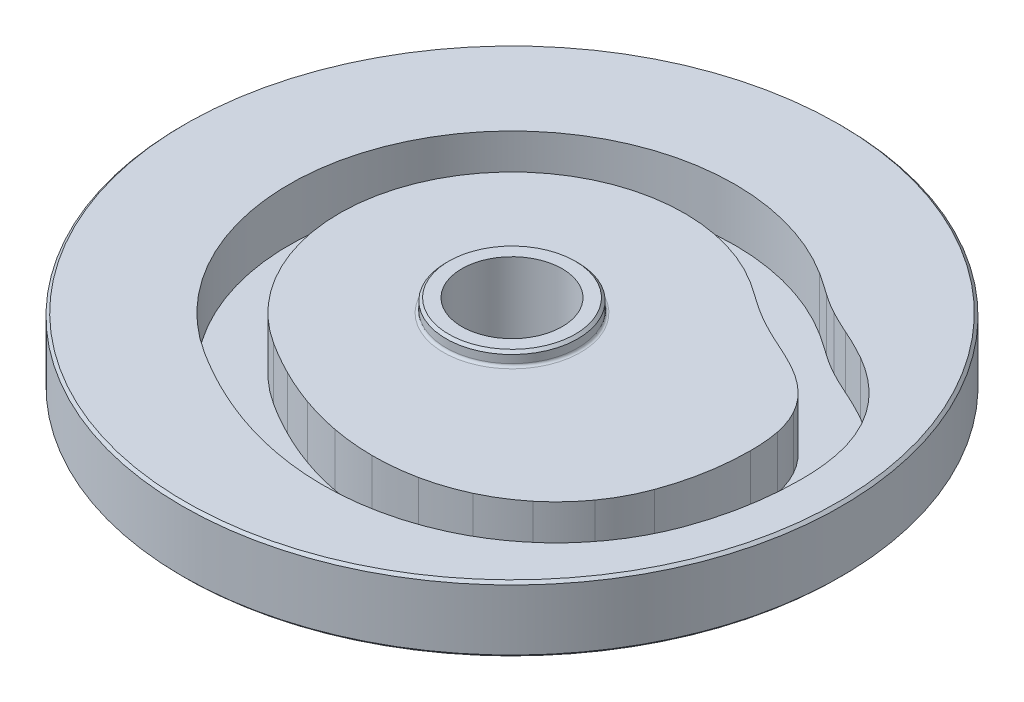
SolidWorks part; units mm, degrees
ref_plane "Front" through (0, 0, 0) normal (0, 0, 1) x (1, 0, 0)
ref_plane "Top" through (0, 0, 0) normal (0, 1, 0) x (1, 0, 0)
ref_plane "Right" through (0, 0, 0) normal (1, 0, 0) x (0, 0, -1)
other "Configuration Table"
sketch "Sketch1" plane through (0, 0, 0) normal (0, 0, 1) x (1, 0, 0)
  line L0 (0, -30350) -> (0, 355) construction
  line L1 (19.05, 5) -> (24, 5)
  line L2 (24, 5) -> (25, 4)
  line L3 (25, 4) -> (25, 1)
  line L4 (26, 0) -> (124, 0)
  line L5 (124, 0) -> (125, -1)
  line L6 (125, -1) -> (125, -24)
  line L7 (125, -24) -> (124, -25)
  line L8 (124, -25) -> (26, -25)
  line L9 (25, -26) -> (25, -29)
  line L10 (25, -29) -> (24, -30)
  line L11 (24, -30) -> (19.05, -30)
  line L12 (19.05, -30) -> (19.05, 5)
  arc A0 (25, 1) -> (26, 0) centre (26, 1) ccw
  arc A1 (26, -25) -> (25, -26) centre (26, -26) ccw
revolve "Base-Revolve" add sketch "Sketch1" angle 360 about L0
sketch "Sketch2" plane through (0, 0, 0) normal (0, 1, 0) x (1, 0, 0)
  line L0 (0, 0) -> (100, 0) construction
  arc A0 (100, 0) -> (98.8357, 13.0115) centre (35.1621, 0.756) ccw
  arc A1 (98.8357, 13.0115) -> (94.4055, 25.2692) centre (56.5582, 4.6609) ccw
  arc A2 (94.4055, 25.2692) -> (86.4082, 35.5582) centre (57.7012, 4.9924) ccw
  arc A3 (86.4082, 35.5582) -> (76.1666, 43.0686) centre (49.5088, -4.0212) ccw
  arc A4 (76.1666, 43.0686) -> (65.7386, 48.2775) centre (17.0985, -62.1401) ccw
  arc A5 (65.7386, 48.2775) -> (56.4654, 52.7493) centre (126.41, 185.9441) cw
  arc A6 (56.4654, 52.7493) -> (48.2764, 57.8032) centre (97.8381, 128.9475) cw
  arc A7 (48.2764, 57.8032) -> (40.2312, 63.2965) centre (-118.4006, -177.6649) ccw
  arc A8 (40.2312, 63.2965) -> (-40.2312, -63.2965) centre (0, 0) ccw
  arc A9 (-40.2312, -63.2965) -> (-27.3421, -70.6474) centre (40.8941, 63.9741) ccw
  arc A10 (-27.3421, -70.6474) -> (-12.9935, -76.8335) centre (29.3243, 41.0558) ccw
  arc A11 (-12.9935, -76.8335) -> (2.9489, -81.1965) centre (23.1016, 23.7507) ccw
  arc A12 (2.9489, -81.1965) -> (20.2342, -82.8956) centre (20.8417, 12.0552) ccw
  arc A13 (20.2342, -82.8956) -> (38.1992, -81.1273) centre (20.7804, 3.6953) ccw
  arc A14 (38.1992, -81.1273) -> (55.8267, -75.3156) centre (22.0381, -2.4696) ccw
  arc A15 (55.8267, -75.3156) -> (71.86, -65.2672) centre (23.9693, -6.6684) ccw
  arc A16 (71.86, -65.2672) -> (84.9698, -51.2829) centre (25.8253, -8.9741) ccw
  arc A17 (84.9698, -51.2829) -> (93.9693, -34.202) centre (26.92, -9.7867) ccw
  arc A18 (93.9693, -34.202) -> (100, 0) centre (0, 0) ccw
extrude "Cut-Extrude-Thin1" cut sketch "Sketch2" along normal blind 15 and the other way blind 20 thin
